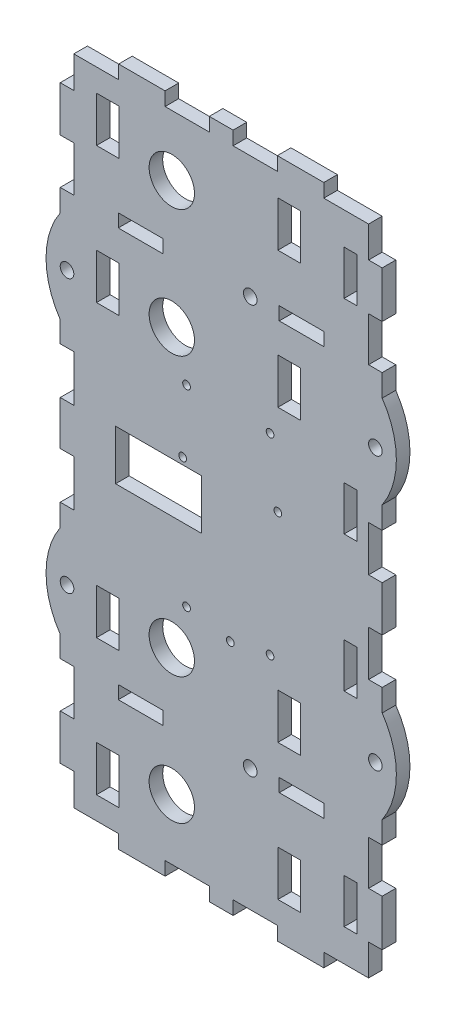
SolidWorks part; units mm, degrees
material "Balsa"
ref_plane "Alzado" through (0, 0, 0) normal (0, 0, 1) x (1, 0, 0)
ref_plane "Planta" through (0, 0, 0) normal (0, 1, 0) x (1, 0, 0)
ref_plane "Vista lateral" through (0, 0, 0) normal (1, 0, 0) x (0, 0, -1)
sketch "Croquis1" plane through (0, 0, 0) normal (0, 0, 1) x (1, 0, 0)
  line L0 (195.4801, 182.0285) -> (195.4801, 175.0285)
  line L1 (195.4801, 175.0285) -> (192.4801, 175.0285)
  line L2 (192.4801, 175.0285) -> (192.4801, 165.0285)
  line L3 (192.4801, 165.0285) -> (195.4801, 165.0285)
  line L4 (195.4801, 165.0285) -> (195.4801, 155.0285)
  line L5 (195.4801, 155.0285) -> (192.4801, 155.0285)
  line L6 (192.4801, 114.9035) -> (192.4801, 105.1535)
  line L7 (192.4801, 65.0285) -> (195.4801, 65.0285)
  line L8 (195.4801, 65.0285) -> (195.4801, 55.0285)
  line L9 (195.4801, 55.0285) -> (192.4801, 55.0285)
  line L10 (192.4801, 55.0285) -> (192.4801, 45.0285)
  line L11 (192.4801, 45.0285) -> (195.4801, 45.0285)
  line L12 (195.4801, 38.0286) -> (195.4801, 45.0285)
  line L13 (260.48, 182.0286) -> (260.48, 175.1536)
  line L14 (263.48, 125.0286) -> (260.48, 125.0286)
  line L15 (260.48, 125.0286) -> (260.48, 115.0286)
  line L16 (260.48, 115.0286) -> (263.48, 115.0286)
  line L17 (263.48, 115.0286) -> (263.48, 105.0286)
  line L18 (263.48, 105.0286) -> (260.48, 105.0286)
  line L19 (260.48, 105.0286) -> (260.48, 95.0286)
  line L20 (260.48, 95.0286) -> (263.48, 95.0286)
  line L21 (260.48, 64.9036) -> (260.48, 55.1536)
  line L22 (260.48, 38.0286) -> (260.48, 44.9036)
  line L23 (225.355, 185.0286) -> (230.605, 185.0286)
  line L24 (230.605, 182.0286) -> (230.605, 185.0286)
  line L25 (225.355, 185.0286) -> (225.355, 182.0285)
  line L26 (205.3551, 185.0285) -> (215.6051, 185.0285)
  line L27 (205.3551, 185.0285) -> (205.3551, 182.0285)
  line L28 (205.3551, 182.0285) -> (195.4801, 182.0285)
  line L29 (215.6051, 185.0285) -> (215.6051, 182.0285)
  line L30 (215.6051, 182.0285) -> (225.355, 182.0285)
  line L31 (240.355, 185.0286) -> (250.605, 185.0286)
  line L32 (250.605, 185.0286) -> (250.605, 182.0286)
  line L33 (250.605, 182.0286) -> (260.48, 182.0286)
  line L34 (240.355, 182.0286) -> (230.605, 182.0286)
  line L35 (240.355, 182.0286) -> (240.355, 185.0286)
  line L36 (225.355, 35.0286) -> (230.605, 35.0286)
  line L37 (230.605, 38.0286) -> (230.605, 35.0286)
  line L38 (225.355, 35.0286) -> (225.355, 38.0286)
  line L39 (205.3551, 35.0286) -> (215.6051, 35.0286)
  line L40 (205.3551, 35.0286) -> (205.3551, 38.0286)
  line L41 (205.3551, 38.0286) -> (195.4801, 38.0286)
  line L42 (215.6051, 35.0286) -> (215.6051, 38.0286)
  line L43 (215.6051, 38.0286) -> (225.355, 38.0286)
  line L44 (240.355, 35.0286) -> (250.605, 35.0286)
  line L45 (250.605, 35.0286) -> (250.605, 38.0286)
  line L46 (250.605, 38.0286) -> (260.48, 38.0286)
  line L47 (240.355, 38.0286) -> (230.605, 38.0286)
  line L48 (240.355, 38.0286) -> (240.355, 35.0286)
  line L49 (263.48, 44.9036) -> (263.48, 55.1536)
  line L50 (263.48, 44.9036) -> (260.48, 44.9036)
  line L51 (263.48, 55.1536) -> (260.48, 55.1536)
  line L52 (263.48, 64.9036) -> (260.48, 64.9036)
  line L53 (260.48, 164.9036) -> (260.48, 155.1536)
  line L54 (263.48, 155.1536) -> (260.48, 155.1536)
  line L55 (263.48, 164.9036) -> (263.48, 175.1536)
  line L56 (263.48, 164.9036) -> (260.48, 164.9036)
  line L57 (263.48, 175.1536) -> (260.48, 175.1536)
  line L58 (195.4801, 94.9035) -> (195.4801, 105.1535)
  line L59 (195.4801, 94.9035) -> (192.4801, 94.9035)
  line L60 (195.4801, 105.1535) -> (192.4801, 105.1535)
  line L61 (195.4801, 114.9035) -> (195.4801, 125.1535)
  line L62 (195.4801, 114.9035) -> (192.4801, 114.9035)
  line L63 (195.4801, 125.1535) -> (192.4801, 125.1535)
  line L64 (210.0952, 63.5785) -> (215.1801, 63.5785)
  line L65 (215.1801, 63.5785) -> (215.1801, 65.1761)
  line L66 (215.1801, 65.1761) -> (215.1801, 66.4785)
  line L67 (215.1801, 66.4785) -> (210.0952, 66.4785)
  line L68 (210.0952, 66.4785) -> (205.2801, 66.4785)
  line L69 (205.2801, 66.4785) -> (205.2801, 65.1761)
  line L70 (205.2801, 65.1761) -> (205.2801, 63.5785)
  line L71 (205.2801, 63.5785) -> (210.0952, 63.5785)
  line L72 (245.5951, 63.5785) -> (250.68, 63.5785)
  line L73 (250.68, 63.5785) -> (250.68, 65.1762)
  line L74 (250.68, 65.1762) -> (250.68, 66.4785)
  line L75 (250.68, 66.4785) -> (245.5951, 66.4785)
  line L76 (245.5951, 66.4785) -> (240.78, 66.4785)
  line L77 (240.78, 66.4785) -> (240.78, 65.1762)
  line L78 (240.78, 65.1762) -> (240.78, 63.5785)
  line L79 (240.78, 63.5785) -> (245.5951, 63.5785)
  line L80 (210.0952, 153.6752) -> (215.1801, 153.6752)
  line L81 (215.1801, 153.6752) -> (215.1801, 155.2728)
  line L82 (215.1801, 155.2728) -> (215.1801, 156.5752)
  line L83 (215.1801, 156.5752) -> (210.0952, 156.5752)
  line L84 (210.0952, 156.5752) -> (205.2801, 156.5752)
  line L85 (205.2801, 156.5752) -> (205.2801, 155.2728)
  line L86 (205.2801, 155.2728) -> (205.2801, 153.6752)
  line L87 (205.2801, 153.6752) -> (210.0952, 153.6752)
  line L88 (245.8649, 153.6752) -> (250.68, 153.6752)
  line L89 (250.68, 153.6752) -> (250.68, 155.2729)
  line L90 (250.68, 155.2729) -> (250.68, 156.5752)
  line L91 (250.68, 156.5752) -> (245.8649, 156.5752)
  line L92 (245.8649, 156.5752) -> (240.78, 156.5752)
  line L93 (240.78, 156.5752) -> (240.78, 155.2729)
  line L94 (240.78, 155.2729) -> (240.78, 153.6752)
  line L95 (240.78, 153.6752) -> (245.8649, 153.6752)
  line L96 (207.4876, 115.5285) -> (204.6876, 115.5285)
  line L97 (204.6876, 115.5285) -> (204.6876, 110.2285)
  line L98 (204.6876, 110.2285) -> (204.6876, 104.5285)
  line L99 (204.6876, 104.5285) -> (207.4876, 104.5285)
  line L100 (207.4876, 104.5285) -> (210.6876, 104.5285)
  line L101 (210.6876, 104.5285) -> (210.6876, 109.8285)
  line L102 (210.6876, 109.8285) -> (210.6876, 115.5285)
  line L103 (210.6876, 115.5285) -> (207.4876, 115.5285)
  line L104 (263.48, 125.0286) -> (263.48, 129.909)
  line L105 (263.48, 150.2732) -> (263.48, 155.1536)
  line L106 (263.48, 64.9036) -> (263.48, 69.784)
  line L107 (263.48, 90.1482) -> (263.48, 95.0286)
  line L108 (192.4801, 150.1481) -> (192.4801, 155.0285)
  line L109 (192.4801, 90.0231) -> (192.4801, 94.9035)
  line L110 (192.4801, 125.1535) -> (192.4801, 129.7839)
  line L111 (192.4801, 65.0285) -> (192.4801, 69.6589)
  circle A0 centre (207.6876, 110.0285) radius 0.4
  circle A20 centre (261.98, 140.0911) radius 1.5
  arc A22 (263.48, 129.909) -> (263.48, 150.2732) centre (248.48, 140.0911) ccw
  circle A23 centre (261.98, 79.9661) radius 1.5
  arc A24 (263.48, 69.784) -> (263.48, 90.1482) centre (248.48, 79.9661) ccw
  circle A25 centre (193.9801, 139.966) radius 1.5
  arc A26 (192.4801, 150.1481) -> (192.4801, 129.7839) centre (207.4801, 139.966) ccw
  circle A27 centre (193.9801, 79.841) radius 1.5
  arc A28 (192.4801, 90.0231) -> (192.4801, 69.6589) centre (207.4801, 79.841) ccw
  circle A29 centre (234.38, 155.1252) radius 1.5
  circle A30 centre (234.38, 65.0285) radius 1.5
  circle A31 centre (193.9801, 139.966) radius 1.5
  circle A33 centre (261.98, 140.0911) radius 1.5
  circle A35 centre (261.98, 79.9661) radius 1.5
  circle A36 centre (234.38, 65.0285) radius 1.5061
  circle A37 centre (193.9801, 79.841) radius 1.5
  circle A41 centre (234.38, 155.1252) radius 1.5
  dimension "D1" = 149.9999
extrude "Saliente-Extruir1" add sketch "Croquis1" along normal mid plane 3
sketch "Croquis3" plane through (0, 0, -1.5) normal (0, 0, -1) x (-1, 0, 0)
  line L1 (-210.6876, 115.5285) -> (-223.6876, 115.5285)
  line L2 (-210.6876, 115.5285) -> (-210.6876, 104.5285)
  line L3 (-210.6876, 104.5285) -> (-223.6876, 104.5285)
  line L4 (-223.6876, 115.5285) -> (-223.6876, 104.5285)
  dimension "D1" = 13
extrude "Cortar-Extruir2" cut sketch "Croquis3" against normal blind 10
sketch "Croquis7" plane through (0, 0, -1.5) normal (0, 0, -1) x (-1, 0, 0)
  line L1 (-192.4801, 125.1535) -> (-192.4801, 129.7839) construction
  line L2 (-223.6876, 115.5285) -> (-204.6876, 115.5285) construction
  line L3 (-268.4722, 110.0286) -> (-177.2198, 110.0286) construction
  point P0 (-220.3401, 131.2085)
  point P5 (-238.7601, 131.2085)
  point P8 (-220.3401, 88.8486)
  point P9 (-238.7601, 88.8486)
  dimension "D1" = 27.86
  dimension "D2" = 15.68
  dimension "D3" = 18.42
hole_wizard "Taladro de margen para M1.61" positions "Croquis8" profile "Croquis9" hole size "M1.6" standard "Ansi Metric" end condition through all
sketch "Croquis8" plane through (0, 0, -1.5) normal (0, 0, -1) x (-1, 0, 0)
  point P0 (-238.7601, 131.2085)
  point P3 (-220.3401, 131.2085)
  point P6 (-220.3401, 88.8486)
  point P9 (-238.7601, 88.8486)
sketch "Croquis9" plane through (238.7601, 131.2085, -1.5) normal (1, 0, 0) x (0, 1, 0)
  line L0 (0, 0) -> (0, 3)
  line L1 (0, 3) -> (0.85, 3)
  line L2 (0.85, 3) -> (0.85, 0.025)
  line L3 (0.85, 0.025) -> (0.875, 0)
  line L5 (0.875, 0) -> (0, 0)
  line L6 (-0.85, 0.025) -> (-0.875, 0) construction
  line L11 (0, -6.35) -> (0, 107.95) construction
  dimension "Diámetro de taladro hasta el siguiente" = 1.7
  dimension "Profundidad de taladro hasta el siguiente" = 3
  dimension "Diámetro de avellanado cercano" = 1.75
  dimension "Ángulo de avellanado cercano" = 90
sketch "Croquis10" plane through (0, 0, -1.5) normal (0, 0, -1) x (-1, 0, 0)
  line L0 (-192.4801, 125.1535) -> (-192.4801, 129.7839) construction
  line L1 (-205.4801, 137.0286) -> (-200.4801, 137.0286)
  line L2 (-205.4801, 137.0286) -> (-205.4801, 147.0286)
  line L3 (-205.4801, 147.0286) -> (-200.4801, 147.0286)
  line L4 (-200.4801, 137.0286) -> (-200.4801, 147.0286)
  line L5 (-227.98, 185.0286) -> (-227.98, 35.0286) construction
  line L6 (-205.4801, 167.0286) -> (-205.4801, 177.0286)
  line L7 (-205.4801, 167.0286) -> (-200.4801, 167.0286)
  line L8 (-200.4801, 167.0286) -> (-200.4801, 177.0286)
  line L9 (-205.4801, 177.0286) -> (-200.4801, 177.0286)
  line L10 (-263.48, 110.0286) -> (-191.049, 110.0286) construction
  line L11 (-263.48, 115.0286) -> (-263.48, 105.0286) construction
  line L12 (-205.4801, 73.0286) -> (-200.4801, 73.0286)
  line L13 (-200.4801, 83.0286) -> (-200.4801, 73.0286)
  line L14 (-205.4801, 83.0286) -> (-200.4801, 83.0286)
  line L15 (-205.4801, 83.0286) -> (-205.4801, 73.0286)
  line L16 (-205.4801, 53.0286) -> (-200.4801, 53.0286)
  line L17 (-200.4801, 53.0286) -> (-200.4801, 43.0286)
  line L18 (-205.4801, 43.0286) -> (-200.4801, 43.0286)
  line L19 (-205.4801, 53.0286) -> (-205.4801, 43.0286)
  line L20 (-225.355, 185.0286) -> (-230.605, 185.0286) construction
  line L21 (-225.355, 35.0286) -> (-230.605, 35.0286) construction
  line L38 (-245.4801, 53.0286) -> (-240.4801, 53.0286)
  line L39 (-240.4801, 53.0286) -> (-240.4801, 43.0286)
  line L40 (-245.4801, 43.0286) -> (-240.4801, 43.0286)
  line L41 (-245.4801, 53.0286) -> (-245.4801, 43.0286)
  line L42 (-245.4801, 73.0286) -> (-240.4801, 73.0286)
  line L43 (-240.4801, 83.0286) -> (-240.4801, 73.0286)
  line L44 (-245.4801, 83.0286) -> (-240.4801, 83.0286)
  line L45 (-245.4801, 83.0286) -> (-245.4801, 73.0286)
  line L46 (-245.4801, 167.0286) -> (-245.4801, 177.0286)
  line L47 (-245.4801, 177.0286) -> (-240.4801, 177.0286)
  line L48 (-240.4801, 167.0286) -> (-240.4801, 177.0286)
  line L49 (-245.4801, 167.0286) -> (-240.4801, 167.0286)
  line L50 (-245.4801, 137.0286) -> (-245.4801, 147.0286)
  line L51 (-245.4801, 137.0286) -> (-240.4801, 137.0286)
  line L52 (-240.4801, 137.0286) -> (-240.4801, 147.0286)
  line L53 (-245.4801, 147.0286) -> (-240.4801, 147.0286)
  point P7 (-200.4801, 142.0286)
  dimension "D1" = 5
  dimension "D2" = 10
  dimension "D3" = 8
  dimension "D4" = 32
  dimension "D5" = 2
  dimension "D6" = 2
extrude "Cortar-Extruir3" cut sketch "Croquis10" against normal blind 10
sketch "Croquis11" plane through (0, 0, -1.5) normal (0, 0, -1) x (-1, 0, 0)
  point P0 (-219.48, 117.0291)
  point P1 (-240.48, 117.0291)
  point P3 (-229.98, 87.0291)
hole_wizard "Taladro de margen para M1.62" positions "Croquis12" profile "Croquis13" hole size "M1.6" standard "Ansi Metric"
sketch "Croquis12" plane through (0, 0, -1.5) normal (0, 0, -1) x (-1, 0, 0)
  point P0 (-240.48, 117.0291)
  point P3 (-219.48, 117.0291)
  point P6 (-229.98, 87.0291)
  point P9 (-170.0932, 124.8709)
sketch "Croquis13" plane through (240.48, 117.0291, -1.5) normal (1, 0, 0) x (0, 1, 0)
  line L0 (0, 0) -> (0, 10.5107)
  line L1 (0, 10.5107) -> (0.85, 10)
  line L2 (0.85, 10) -> (0.85, 0)
  line L5 (0.85, 0) -> (0, 0)
  line L10 (0, 10.5107) -> (-0.85, 10) construction
  line L11 (0, -6.35) -> (0, 107.95) construction
  dimension "Diámetro de taladro" = 1.7
  dimension "Profundidad de taladro" = 10
  dimension "Ángulo de perforador" = 118
sketch "Croquis14" plane through (0, 0, -1.5) normal (0, 0, -1) x (-1, 0, 0)
  line L0 (-263.48, 170.0286) -> (-192.4801, 170.0285) construction
  line L1 (-263.48, 164.9036) -> (-263.48, 175.1536) construction
  line L2 (-192.4801, 175.0285) -> (-192.4801, 165.0285) construction
  line L3 (-263.48, 110.0286) -> (-192.4801, 110.0286) construction
  line L4 (-257.88, 165.1286) -> (-255.08, 165.1286)
  line L5 (-257.88, 165.1286) -> (-257.88, 174.9286)
  line L6 (-257.88, 174.9286) -> (-255.08, 174.9286)
  line L7 (-255.08, 165.1286) -> (-255.08, 174.9286)
  line L8 (-257.88, 165.1286) -> (-255.08, 174.9286) construction
  line L9 (-257.88, 174.9286) -> (-255.08, 165.1286) construction
  line L10 (-263.48, 115.0286) -> (-263.48, 105.0286) construction
  line L11 (-192.4801, 114.9035) -> (-192.4801, 105.1535) construction
  line L12 (-257.88, 45.1286) -> (-255.08, 45.1286)
  line L13 (-255.08, 54.9286) -> (-255.08, 45.1286)
  line L14 (-257.88, 54.9286) -> (-255.08, 54.9286)
  line L15 (-257.88, 54.9286) -> (-257.88, 45.1286)
  line L16 (-256.48, 170.0286) -> (-256.48, 54.9286) construction
  line L17 (-257.88, 90.1286) -> (-255.08, 90.1286)
  line L18 (-257.88, 120.1286) -> (-255.08, 120.1286)
  line L19 (-257.88, 120.1286) -> (-257.88, 129.9286)
  line L20 (-257.88, 129.9286) -> (-255.08, 129.9286)
  line L21 (-255.08, 120.1286) -> (-255.08, 129.9286)
  line L22 (-257.88, 120.1286) -> (-255.08, 129.9286) construction
  line L23 (-257.88, 129.9286) -> (-255.08, 120.1286) construction
  line L24 (-255.08, 99.9286) -> (-255.08, 90.1286)
  line L25 (-257.88, 99.9286) -> (-255.08, 99.9286)
  line L26 (-257.88, 99.9286) -> (-257.88, 90.1286)
  point P6 (-256.48, 170.0286)
  point P23 (-256.48, 125.0286)
  dimension "D1" = 9.8
  dimension "D2" = 2.8
  dimension "D3" = 7
  dimension "D4" = 9.8
  dimension "D5" = 2.8
  dimension "D6" = 15
extrude "Cortar-Extruir4" cut sketch "Croquis14" against normal blind 10
sketch "Croquis15" plane through (0, 0, -1.5) normal (0, 0, -1) x (-1, 0, 0)
  line L0 (-263.48, 110.0286) -> (-247.6521, 110.0286) construction
  line L1 (-263.48, 115.0286) -> (-263.48, 105.0286) construction
  circle A0 centre (-217.0801, 51.4107) radius 5
  circle A1 centre (-217.0801, 79.4107) radius 5
  circle A2 centre (-217.0801, 140.6465) radius 5
  circle A3 centre (-217.0801, 168.6465) radius 5
  dimension "D1" = 10
  dimension "D2" = 2
extrude "Cortar-Extruir5" cut sketch "Croquis15" against normal blind 10
